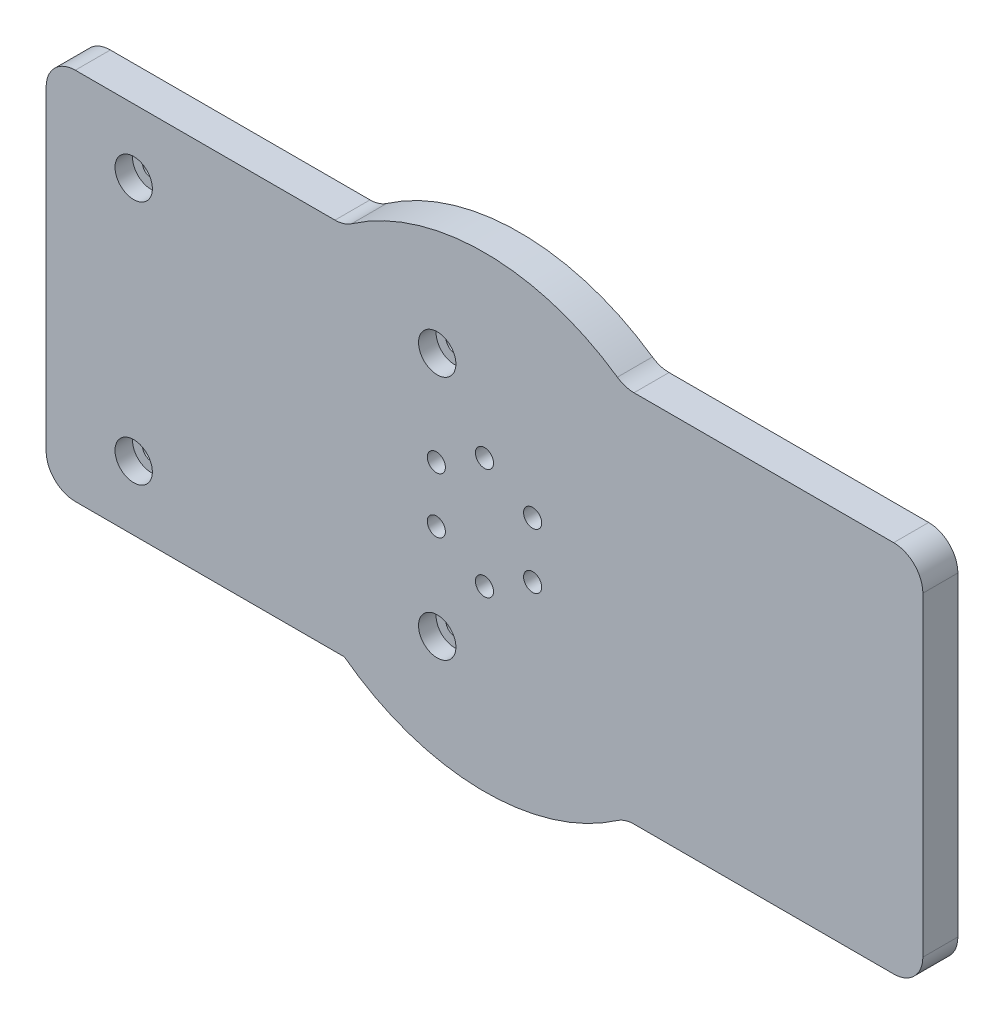
SolidWorks part; units mm, degrees
material "3003 Alloy"
ref_plane "Front Plane" through (0, 0, 0) normal (0, 0, 1) x (1, 0, 0)
ref_plane "Top Plane" through (0, 0, 0) normal (0, 1, 0) x (1, 0, 0)
ref_plane "Right Plane" through (0, 0, 0) normal (1, 0, 0) x (0, 0, -1)
sketch "Sketch1" plane through (0, 0, 0) normal (0, 0, 1) x (1, 0, 0)
  line L1 (0, 0) -> (150.2, 0)
  line L2 (0, 0) -> (0, 64)
  line L3 (0, 64) -> (150.2, 64)
  line L4 (150.2, 0) -> (150.2, 64)
extrude "Boss-Extrude1" add sketch "Sketch1" along normal blind 6
fillet "Fillet1" radius 5 4 edges at (150.2, 0, 3) (150.2, 64, 3) (0, 0, 3) (0, 64, 3)
sketch "Sketch2" plane through (0, 0, 0) normal (0, -1, 0) x (1, 0, 0)
  line L0 (5, 0) -> (145.2, 0) construction
  line L1 (0, 6) -> (60, 6)
  line L2 (0, 6) -> (0, 0)
  line L3 (0, 0) -> (60, 0)
  line L4 (60, 6) -> (60, 0)
extrude "Boss-Extrude2" add sketch "Sketch2" along normal blind 40 and the other way blind 10
fillet "Fillet2" radius 5 2 edges at (0, -40, 3) (60, -40, 3)
sketch "Sketch3" plane through (0, 0, 6) normal (0, 0, 1) x (1, 0, 0)
  circle A0 centre (75.1, 32) radius 40
extrude "Boss-Extrude4" add sketch "Sketch3" against normal blind 6
fillet "Fillet4" radius 5 4 edges at (99.1, 64, 3) (51.1, 64, 3) (99.1, 0, 3) (60, -5.0404, 3)
sketch "Sketch4" plane through (0, 0, 6) normal (0, 0, 1) x (1, 0, 0)
  circle A9 centre (75.1, 41.525) radius 1.55
  circle A10 centre (83.3489, 36.7625) radius 1.55
  circle A11 centre (83.3489, 27.2375) radius 1.55
  circle A12 centre (75.1, 22.475) radius 1.55
  circle A13 centre (66.8511, 27.2375) radius 1.55
  circle A14 centre (66.8511, 36.7625) radius 1.55
  point P16 (75.1, 32)
  point P17 (75.1, 32)
  dimension "D1" = 6
extrude "Cut-Extrude1" cut sketch "Sketch4" against normal through all
sketch "Sketch5" plane through (0, 0, 0) normal (0, 0, -1) x (-1, 0, 0)
  line L0 (-100.7125, 0) -> (0, 0)
  line L8 (-145.2, 0) -> (-100.7125, 0)
  line L9 (-60, -11.8519) -> (-60, -35)
  line L10 (-55, -40) -> (-5, -40)
  line L11 (0, -35) -> (0, 59)
  line L12 (-5, 64) -> (-49.4875, 64)
  line L13 (-100.7125, 64) -> (-145.2, 64)
  line L14 (-150.2, 59) -> (-150.2, 5)
  line L15 (-145.2, 0) -> (-100.7125, 0)
  line L16 (-60, -11.8519) -> (-60, -35)
  line L17 (-55, -40) -> (-5, -40)
  line L18 (0, -35) -> (0, 59)
  line L19 (-5, 64) -> (-49.4875, 64)
  line L20 (-100.7125, 64) -> (-145.2, 64)
  line L21 (-150.2, 59) -> (-150.2, 5)
  circle A0 centre (-75.1, 32) radius 40
  arc A12 (-97.8667, -0.8889) -> (-100.7125, 0) centre (-100.7125, -5) ccw
  arc A13 (-97.8667, -0.8889) -> (-66.1222, -6.9795) centre (-75.1, 32) ccw
  arc A14 (-60, -11.8519) -> (-66.1222, -6.9795) centre (-65, -11.8519) ccw
  arc A15 (-60, -35) -> (-55, -40) centre (-55, -35) ccw
  arc A16 (-5, -40) -> (0, -35) centre (-5, -35) ccw
  arc A17 (0, 59) -> (-5, 64) centre (-5, 59) ccw
  arc A18 (-52.3333, 64.8889) -> (-49.4875, 64) centre (-49.4875, 69) ccw
  arc A19 (-52.3333, 64.8889) -> (-97.8667, 64.8889) centre (-75.1, 32) ccw
  arc A20 (-100.7125, 64) -> (-97.8667, 64.8889) centre (-100.7125, 69) ccw
  arc A21 (-145.2, 64) -> (-150.2, 59) centre (-145.2, 59) ccw
  arc A22 (-150.2, 5) -> (-145.2, 0) centre (-145.2, 5) ccw
  arc A23 (-97.8667, -0.8889) -> (-100.7125, 0) centre (-100.7125, -5) ccw
  arc A24 (-97.8667, -0.8889) -> (-66.1222, -6.9795) centre (-75.1, 32) ccw
  arc A25 (-60, -11.8519) -> (-66.1222, -6.9795) centre (-65, -11.8519) ccw
  arc A26 (-60, -35) -> (-55, -40) centre (-55, -35) ccw
  arc A27 (-5, -40) -> (0, -35) centre (-5, -35) ccw
  arc A28 (0, 59) -> (-5, 64) centre (-5, 59) ccw
  arc A29 (-52.3333, 64.8889) -> (-49.4875, 64) centre (-49.4875, 69) ccw
  arc A30 (-52.3333, 64.8889) -> (-97.8667, 64.8889) centre (-75.1, 32) ccw
  arc A31 (-100.7125, 64) -> (-97.8667, 64.8889) centre (-100.7125, 69) ccw
  arc A32 (-145.2, 64) -> (-150.2, 59) centre (-145.2, 59) ccw
  arc A33 (-150.2, 5) -> (-145.2, 0) centre (-145.2, 5) ccw
  arc M28 (-66.1222, -6.9795) -> (-60, -11.8519) centre (-65, -11.8519) cw
  line M29 (-60, -11.8519) -> (-60, -35)
  arc M30 (-60, -35) -> (-55, -40) centre (-55, -35) ccw
  line M31 (-55, -40) -> (-5, -40)
  arc M32 (-5, -40) -> (0, -35) centre (-5, -35) ccw
  line M33 (0, -35) -> (0, 59)
  dimension "D1" = 0
extrude "Cut-Extrude2" cut sketch "Sketch5" against normal blind 10 contours A0 L0 M28 M29 M30 M31 M32 M33
fillet "Fillet5" radius 5 1 edges at (0, 0, 3)
sketch "Sketch6" plane through (0, 0, 6) normal (0, 0, 1) x (1, 0, 0)
  circle A0 centre (15, 11) radius 1.5
  circle A1 centre (15, 53) radius 1.5
extrude "Cut-Extrude3" cut sketch "Sketch6" against normal through all
sketch "Sketch7" plane through (0, 0, 6) normal (0, 0, 1) x (1, 0, 0)
  circle A0 centre (67, 53) radius 1.5
  circle A1 centre (67, 11) radius 1.5
extrude "Cut-Extrude4" cut sketch "Sketch7" against normal through all
sketch "Sketch9" plane through (0, 0, 6) normal (0, 0, 1) x (1, 0, 0)
  circle A0 centre (15, 53) radius 3.2
  circle A1 centre (67, 53) radius 3.2
  circle A2 centre (15, 11) radius 3.2
  circle A3 centre (67, 11) radius 3.2
extrude "Cut-Extrude5" cut sketch "Sketch9" against normal blind 3
